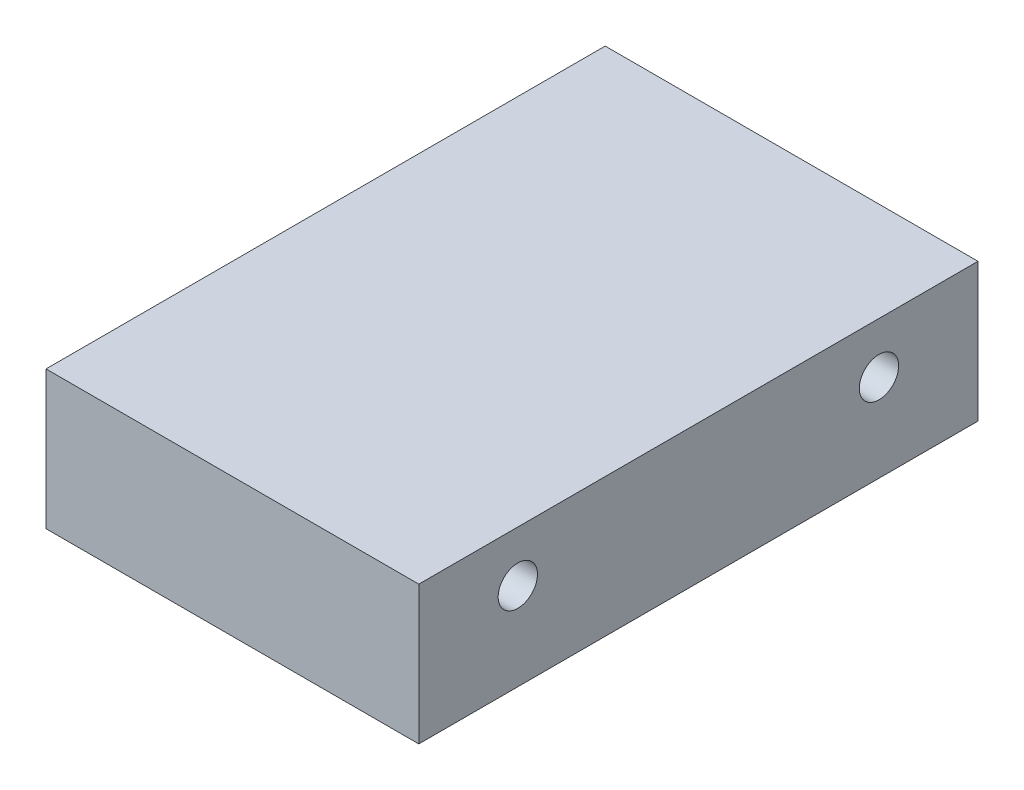
SolidWorks part; units mm, degrees
material "Plain Carbon Steel"
ref_plane "Front Plane" through (0, 0, 0) normal (0, 0, 1) x (1, 0, 0)
ref_plane "Top Plane" through (0, 0, 0) normal (0, 1, 0) x (1, 0, 0)
ref_plane "Right Plane" through (0, 0, 0) normal (1, 0, 0) x (0, 0, -1)
sketch "Sketch1" plane through (0, 0, 0) normal (0, 1, 0) x (1, 0, 0)
  line L1 (50.8, -76.2) -> (-50.8, -76.2)
  line L2 (50.8, -76.2) -> (50.8, 76.2)
  line L3 (50.8, 76.2) -> (-50.8, 76.2)
  line L4 (-50.8, -76.2) -> (-50.8, 76.2)
  line L5 (50.8, -76.2) -> (-50.8, 76.2) construction
  line L6 (50.8, 76.2) -> (-50.8, -76.2) construction
  point P0 (0, 0)
  dimension "D1" = 152.4
  dimension "D2" = 101.6
extrude "Boss-Extrude1" add sketch "Sketch1" along normal blind 37.719
sketch "Sketch2" plane through (50.8, 0, 0) normal (1, 0, 0) x (0, 0, -1)
  line L0 (-76.2, 37.719) -> (-76.2, 0) construction
  line L2 (-76.2, 37.719) -> (76.2, 37.719) construction
  line L3 (-76.2, 23.876) -> (-49.2125, 23.876) construction
  line L4 (-49.2125, 23.876) -> (49.2125, 23.876) construction
  line L5 (49.2125, 23.876) -> (76.2, 23.876) construction
  line L6 (76.2, 37.719) -> (76.2, 0) construction
  circle A0 centre (-49.2125, 23.876) radius 5.3581
  circle A1 centre (49.2125, 23.876) radius 5.3581
  dimension "D3" = 10.7163
  dimension "D1" = 26.9875
  dimension "D2" = 13.843
extrude "Cut-Extrude1" cut sketch "Sketch2" against normal through all
